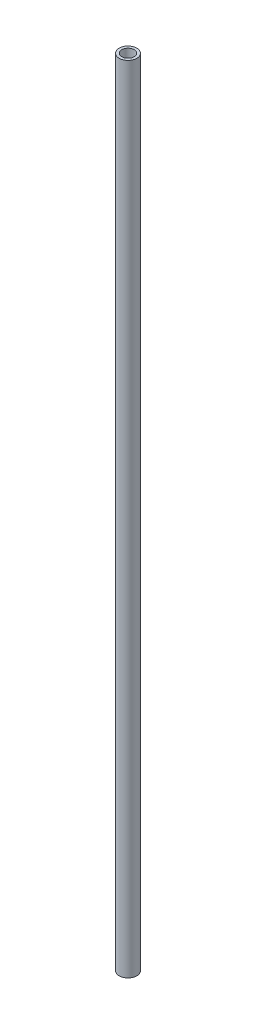
SolidWorks part; units mm, degrees
material "Thornel Mat VMA"
ref_plane "Front Plane" through (0, 0, 0) normal (0, 0, 1) x (1, 0, 0)
ref_plane "Top Plane" through (0, 0, 0) normal (0, 1, 0) x (1, 0, 0)
ref_plane "Right Plane" through (0, 0, 0) normal (1, 0, 0) x (0, 0, -1)
sketch "Sketch1" plane through (0, 0, 0) normal (0, 1, 0) x (1, 0, 0)
  circle A0 centre (0, 0) radius 5
  circle A1 centre (0, 0) radius 3.5
  dimension "D1" = 10
  dimension "D2" = 1.5
extrude "Boss-Extrude1" add sketch "Sketch1" along normal blind 450
